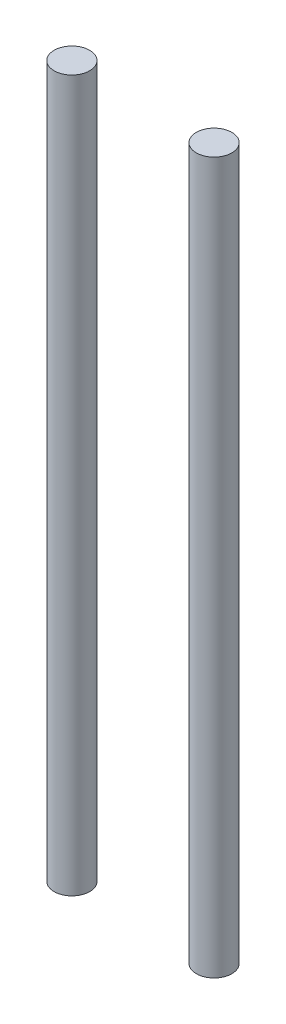
SolidWorks part; units mm, degrees
ref_plane "前视基准面" through (0, 0, 0) normal (0, 0, 1) x (1, 0, 0)
ref_plane "上视基准面" through (0, 0, 0) normal (0, 1, 0) x (1, 0, 0)
ref_plane "右视基准面" through (0, 0, 0) normal (1, 0, 0) x (0, 0, -1)
other "Configuration Table"
sketch "草图1" plane through (0, 0, 0) normal (0, 1, 0) x (1, 0, 0)
  line L0 (-50, 0) -> (50, 0) construction
  circle A0 centre (-50, 0) radius 12.5
  circle A1 centre (50, 0) radius 12.5
  dimension "D2" = 25
  dimension "D3" = 25
  dimension "D1" = 100
extrude "凸台-拉伸1" add sketch "草图1" along normal blind 500
